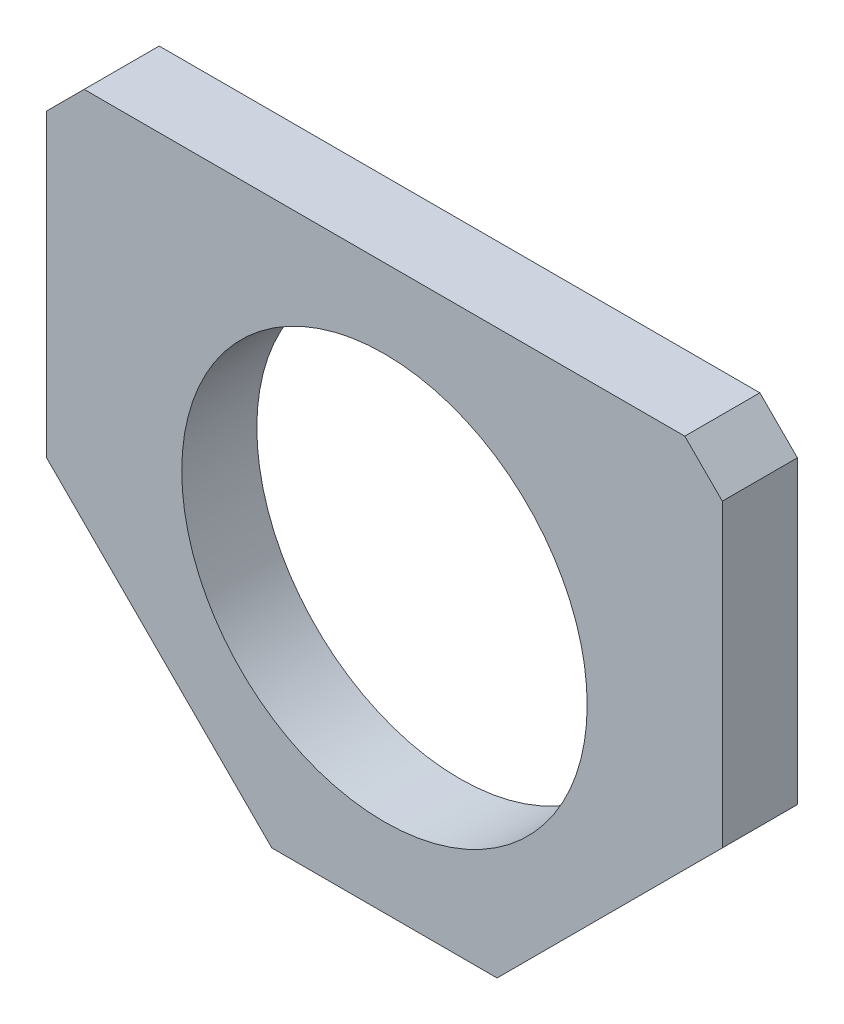
SolidWorks part; units mm, degrees
ref_plane "Front Plane" through (0, 0, 0) normal (0, 0, 1) x (1, 0, 0)
ref_plane "Top Plane" through (0, 0, 0) normal (0, 1, 0) x (1, 0, 0)
ref_plane "Right Plane" through (0, 0, 0) normal (1, 0, 0) x (0, 0, -1)
sketch "Sketch1" plane through (0, 0, 0) normal (0, 0, 1) x (1, 0, 0)
  line L1 (-9, -7.5) -> (9, -7.5)
  line L2 (-9, -7.5) -> (-9, 7.5)
  line L3 (-9, 7.5) -> (9, 7.5)
  line L4 (9, -7.5) -> (9, 7.5)
  line L5 (-9, -7.5) -> (9, 7.5) construction
  line L6 (-9, 7.5) -> (9, -7.5) construction
  point P0 (0, 0)
  dimension "D1" = 18
  dimension "D2" = 15
extrude "Boss-Extrude1" add sketch "Sketch1" along normal blind 2
chamfer "Chamfer1" distance 1 angle 45 2 edges at (9, 7.5, 1) (-9, 7.5, 1)
hole_wizard "M12x1.25 Tapped Hole1" positions "Sketch3" profile "Sketch2" tap size "M12x1.25" standard "Ansi Metric"
sketch "Sketch3" plane through (0, 0, 2) normal (0, 0, 1) x (1, 0, 0)
  line L0 (8, 7.5) -> (-8, 7.5) construction
  line L1 (9, -7.5) -> (9, 6.5) construction
  point P0 (0, 0)
  dimension "D1" = 7.5
  dimension "D2" = 9
sketch "Sketch2" plane through (0, 0, 2) normal (1, 0, 0) x (0, -1, 0)
  line L0 (0, 0) -> (0, 11.9946)
  line L1 (0, 11.9946) -> (5.4, 8.75)
  line L2 (5.4, 8.75) -> (5.4, 0)
  line L5 (5.4, 0) -> (0, 0)
  line L10 (0, 11.9946) -> (-5.4, 8.75) construction
  line L11 (0, -6.35) -> (0, 107.95) construction
  dimension "Tap Drill Dia." = 10.8
  dimension "Tap Drill Depth" = 8.75
  dimension "Drill Angle" = 118
cosmetic thread "Hole Thread1" parameters "D1"=2, "D2"=12
chamfer "Chamfer2" distance 6 angle 45 2 edges at (9, -7.5, 1) (-9, -7.5, 1)
